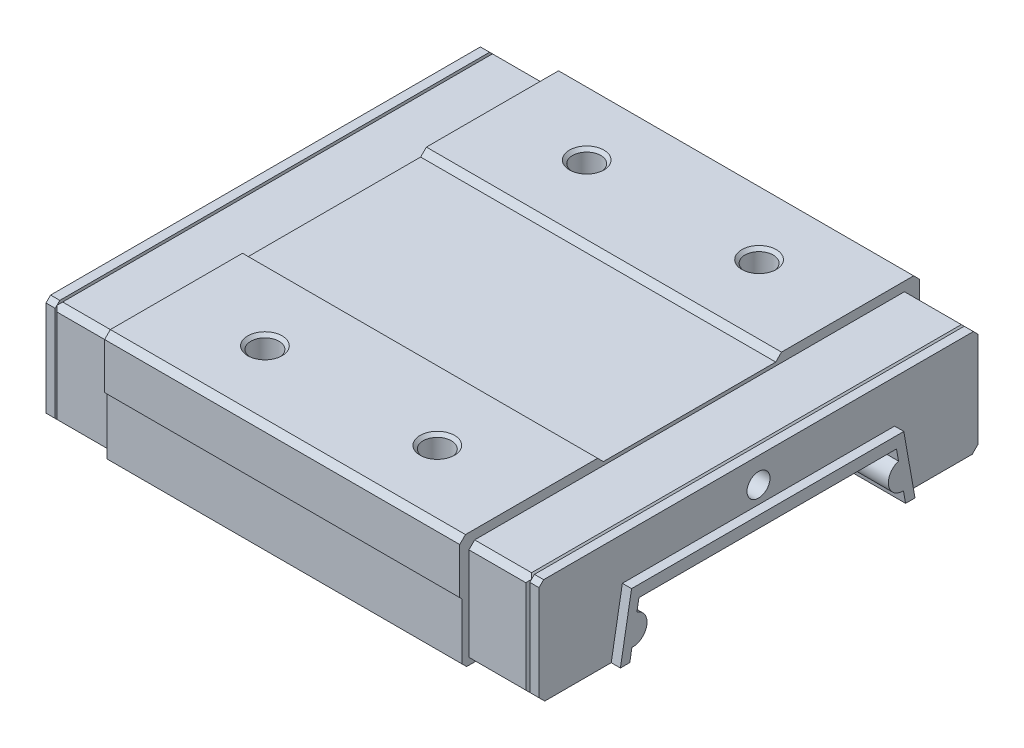
SolidWorks part; units mm, degrees
ref_plane "Plano frontal" through (0, 0, 0) normal (0, 0, 1) x (1, 0, 0)
ref_plane "Plano superior" through (0, 0, 0) normal (0, 1, 0) x (1, 0, 0)
ref_plane "Plano direito" through (0, 0, 0) normal (1, 0, 0) x (0, 0, -1)
ref_plane "Plano1" through (0, 0, 0) normal (1, 0, 0) x (0, 0, -1)
sketch "Esboço1" plane through (0, 0, 0) normal (1, 0, 0) x (0, 0, -1)
  line L0 (-20, 9.5) -> (-20, 5.5)
  line L1 (-20, 5.5) -> (-19.8, 5.3)
  line L2 (-19.8, 5.3) -> (-19.8, 0.4)
  line L3 (-19.8, 0.4) -> (-19.4, 0)
  line L4 (-19.4, 0) -> (19.4, 0)
  line L5 (19.4, 0) -> (19.8, 0.4)
  line L6 (19.8, 0.4) -> (19.8, 5.3)
  line L7 (19.8, 5.3) -> (20, 5.5)
  line L8 (20, 5.5) -> (20, 9.5)
  line L9 (20, 9.5) -> (19.5, 10)
  line L10 (19.5, 10) -> (8, 10)
  line L11 (8, 10) -> (7.5, 9.5)
  line L12 (7.5, 9.5) -> (-7.5, 9.5)
  line L13 (-7.5, 9.5) -> (-8, 10)
  line L14 (-8, 10) -> (-19.5, 10)
  line L15 (-19.5, 10) -> (-20, 9.5)
extrude "Ressalto-extrusão1" add sketch "Esboço1" against normal blind 15.45 and the other way blind 15.45
ref_plane "Plano2" through (-15.45, 0, 0) normal (1, 0, 0) x (0, 0, -1)
sketch "Esboço2" plane through (-15.45, 0, 0) normal (1, 0, 0) x (0, 0, -1)
  line L0 (-19.2, 8.7) -> (-19.2, 0.6)
  line L1 (-19.2, 0.6) -> (-18.6, 0)
  line L2 (-18.6, 0) -> (18.6, 0)
  line L3 (18.6, 0) -> (19.2, 0.6)
  line L4 (19.2, 0.6) -> (19.2, 8.7)
  line L5 (19.2, 8.7) -> (18.7, 9.2)
  line L6 (18.7, 9.2) -> (-18.7, 9.2)
  line L7 (-18.7, 9.2) -> (-19.2, 8.7)
extrude "Ressalto-extrusão2" add sketch "Esboço2" against normal blind 6
ref_plane "Plano3" through (15.45, 0, 0) normal (1, 0, 0) x (0, 0, -1)
sketch "Esboço3" plane through (15.45, 0, 0) normal (1, 0, 0) x (0, 0, -1)
  line L0 (-19.2, 8.7) -> (-19.2, 0.6)
  line L1 (-19.2, 0.6) -> (-18.6, 0)
  line L2 (-18.6, 0) -> (18.6, 0)
  line L3 (18.6, 0) -> (19.2, 0.6)
  line L4 (19.2, 0.6) -> (19.2, 8.7)
  line L5 (19.2, 8.7) -> (18.7, 9.2)
  line L6 (18.7, 9.2) -> (-18.7, 9.2)
  line L7 (-18.7, 9.2) -> (-19.2, 8.7)
extrude "Ressalto-extrusão3" add sketch "Esboço3" along normal blind 6
ref_plane "Plano4" through (0, 0, 0) normal (1, 0, 0) x (0, 0, -1)
sketch "Esboço4" plane through (0, 0, 0) normal (1, 0, 0) x (0, 0, -1)
  line L0 (-12.816, 0) -> (12.816, 0)
  line L1 (12.816, 0) -> (11.8462, 5.5)
  line L2 (11.8462, 5.5) -> (-11.8462, 5.5)
  line L3 (-11.8462, 5.5) -> (-12.816, 0)
extrude "Ressalto-extrusão4" add sketch "Esboço4" against normal blind 22.25 and the other way blind 22.25
ref_plane "Plano5" through (0, 0, 0) normal (1, 0, 0) x (0, 0, -1)
sketch "Esboço5" plane through (0, 0, 0) normal (1, 0, 0) x (0, 0, -1)
  line L0 (-12, 0) -> (12, 0)
  line L1 (12, 0) -> (11.8146, 1.0517)
  line L2 (11.3837, 3.4951) -> (11.2065, 4.5)
  line L3 (11.2065, 4.5) -> (-11.2065, 4.5)
  line L4 (-11.2065, 4.5) -> (-11.3837, 3.4951)
  line L5 (-11.8146, 1.0517) -> (-12, 0)
  arc A0 (11.8146, 1.0517) -> (11.3837, 3.4951) centre (11.75, 2.3) cw
  arc A1 (-11.3837, 3.4951) -> (-11.8146, 1.0517) centre (-11.75, 2.3) cw
extrude "Corte-extrusão1" cut sketch "Esboço5" against normal blind 22.25 and the other way blind 22.25
ref_plane "Plano6" through (0, 0, 14) normal (0, 0, 1) x (1, 0, 0)
sketch "Esboço6" plane through (0, 0, 14) normal (0, 0, 1) x (1, 0, 0)
  line L0 (7.5, 10) -> (9, 10)
  line L1 (9, 10) -> (8.7295, 9.7295)
  line L2 (8.7295, 9.7295) -> (8.7295, 5.8)
  line L3 (8.7295, 5.8) -> (7.5, 5.0901)
  line L4 (7.5, 5.0901) -> (7.5, 10)
  line L5 (7.5, 5.0901) -> (7.5, 10) construction
revolve "Corte-Revolução1" cut sketch "Esboço6" angle 360 about L5
ref_plane "Plano7" through (0, 0, -14) normal (0, 0, 1) x (1, 0, 0)
sketch "Esboço7" plane through (0, 0, -14) normal (0, 0, 1) x (1, 0, 0)
  line L0 (-7.5, 10) -> (-6, 10)
  line L1 (-6, 10) -> (-6.2705, 9.7295)
  line L2 (-6.2705, 9.7295) -> (-6.2705, 5.8)
  line L3 (-6.2705, 5.8) -> (-7.5, 5.0901)
  line L4 (-7.5, 5.0901) -> (-7.5, 10)
  line L5 (-7.5, 5.0901) -> (-7.5, 10) construction
revolve "Corte-Revolução2" cut sketch "Esboço7" angle 360 about L5
ref_plane "Plano8" through (0, 0, 14) normal (0, 0, 1) x (1, 0, 0)
sketch "Esboço8" plane through (0, 0, 14) normal (0, 0, 1) x (1, 0, 0)
  line L0 (-7.5, 10) -> (-6, 10)
  line L1 (-6, 10) -> (-6.2705, 9.7295)
  line L2 (-6.2705, 9.7295) -> (-6.2705, 5.8)
  line L3 (-6.2705, 5.8) -> (-7.5, 5.0901)
  line L4 (-7.5, 5.0901) -> (-7.5, 10)
  line L5 (-7.5, 5.0901) -> (-7.5, 10) construction
revolve "Corte-Revolução3" cut sketch "Esboço8" angle 360 about L5
ref_plane "Plano9" through (0, 0, -14) normal (0, 0, 1) x (1, 0, 0)
sketch "Esboço9" plane through (0, 0, -14) normal (0, 0, 1) x (1, 0, 0)
  line L0 (7.5, 10) -> (9, 10)
  line L1 (9, 10) -> (8.7295, 9.7295)
  line L2 (8.7295, 9.7295) -> (8.7295, 5.8)
  line L3 (8.7295, 5.8) -> (7.5, 5.0901)
  line L4 (7.5, 5.0901) -> (7.5, 10)
  line L5 (7.5, 5.0901) -> (7.5, 10) construction
revolve "Corte-Revolução4" cut sketch "Esboço9" angle 360 about L5
ref_plane "Plano10" through (0, 0, 0) normal (0, 1, 0) x (1, 0, 0)
sketch "Esboço10" plane through (0, 0, 0) normal (0, 1, 0) x (1, 0, 0)
  line L0 (-24.25, -22) -> (24.25, -22)
  line L1 (24.25, -22) -> (24.25, 22)
  line L2 (24.25, 22) -> (-24.25, 22)
  line L3 (-24.25, 22) -> (-24.25, -22)
  line L4 (-23.25, 19.1) -> (-23.25, -19.1)
  line L5 (-23.25, -19.1) -> (-20.65, -19.1)
  line L6 (-20.65, -19.1) -> (-20.65, -21)
  line L7 (-20.65, -21) -> (20.65, -21)
  line L8 (20.65, -21) -> (20.65, -19.1)
  line L9 (20.65, -19.1) -> (23.25, -19.1)
  line L10 (23.25, -19.1) -> (23.25, 19.1)
  line L11 (23.25, 19.1) -> (20.65, 19.1)
  line L12 (20.65, 19.1) -> (20.65, 21)
  line L13 (20.65, 21) -> (-20.65, 21)
  line L14 (-20.65, 21) -> (-20.65, 19.1)
  line L15 (-20.65, 19.1) -> (-23.25, 19.1)
extrude "Corte-extrusão2" cut sketch "Esboço10" along normal blind 11
ref_plane "Plano11" through (0, 0, 0) normal (0, 0, 1) x (1, 0, 0)
sketch "Esboço11" plane through (0, 0, 0) normal (0, 0, 1) x (1, 0, 0)
  line L0 (-20.65, 9.2) -> (-20.65, 8.95)
  line L1 (-20.65, 8.95) -> (-20.4, 9.2)
  line L2 (-20.4, 9.2) -> (-20.65, 9.2)
extrude "Corte-extrusão3" cut sketch "Esboço11" against normal blind 20 and the other way blind 20
ref_plane "Plano12" through (0, 0, 0) normal (0, 0, 1) x (1, 0, 0)
sketch "Esboço12" plane through (0, 0, 0) normal (0, 0, 1) x (1, 0, 0)
  line L0 (20.4, 9.2) -> (20.65, 8.95)
  line L1 (20.65, 8.95) -> (20.65, 9.2)
  line L2 (20.65, 9.2) -> (20.4, 9.2)
extrude "Corte-extrusão4" cut sketch "Esboço12" against normal blind 20 and the other way blind 20
ref_plane "Plano13" through (0, 0, 0) normal (0, 1, 0) x (1, 0, 0)
sketch "Esboço13" plane through (0, 0, 0) normal (0, 1, 0) x (1, 0, 0)
  line L0 (-20.65, 19.2) -> (-20.65, 18.95)
  line L1 (-20.65, 18.95) -> (-20.4, 19.2)
  line L2 (-20.4, 19.2) -> (-20.65, 19.2)
extrude "Corte-extrusão5" cut sketch "Esboço13" along normal blind 10
ref_plane "Plano14" through (0, 0, 0) normal (0, 1, 0) x (1, 0, 0)
sketch "Esboço14" plane through (0, 0, 0) normal (0, 1, 0) x (1, 0, 0)
  line L0 (-20.65, -19.2) -> (-20.4, -19.2)
  line L1 (-20.4, -19.2) -> (-20.65, -18.95)
  line L2 (-20.65, -18.95) -> (-20.65, -19.2)
extrude "Corte-extrusão6" cut sketch "Esboço14" along normal blind 10
ref_plane "Plano15" through (0, 0, 0) normal (0, 1, 0) x (1, 0, 0)
sketch "Esboço15" plane through (0, 0, 0) normal (0, 1, 0) x (1, 0, 0)
  line L0 (20.4, 19.2) -> (20.65, 18.95)
  line L1 (20.65, 18.95) -> (20.65, 19.2)
  line L2 (20.65, 19.2) -> (20.4, 19.2)
extrude "Corte-extrusão7" cut sketch "Esboço15" along normal blind 10
ref_plane "Plano16" through (0, 0, 0) normal (0, 1, 0) x (1, 0, 0)
sketch "Esboço16" plane through (0, 0, 0) normal (0, 1, 0) x (1, 0, 0)
  line L0 (20.4, -19.2) -> (20.65, -19.2)
  line L1 (20.65, -19.2) -> (20.65, -18.95)
  line L2 (20.65, -18.95) -> (20.4, -19.2)
extrude "Corte-extrusão8" cut sketch "Esboço16" along normal blind 10
ref_plane "Plano17" through (0, 0, 0) normal (0, 0, 1) x (1, 0, 0)
sketch "Esboço17" plane through (0, 0, 0) normal (0, 0, 1) x (1, 0, 0)
  line L0 (-21.45, 7) -> (-21.45, 8)
  line L1 (-21.45, 8) -> (-18.95, 8)
  line L2 (-18.95, 8) -> (-18.95, 7)
  line L3 (-18.95, 7) -> (-21.45, 7)
  line L4 (-18.95, 7) -> (-21.45, 7) construction
revolve "Corte-Revolução5" cut sketch "Esboço17" angle 360 about L4
ref_plane "Plano18" through (0, 0, 0) normal (0, 0, 1) x (1, 0, 0)
sketch "Esboço18" plane through (0, 0, 0) normal (0, 0, 1) x (1, 0, 0)
  line L0 (18.95, 7) -> (18.95, 8)
  line L1 (18.95, 8) -> (21.45, 8)
  line L2 (21.45, 8) -> (21.45, 7)
  line L3 (21.45, 7) -> (18.95, 7)
  line L4 (21.45, 7) -> (18.95, 7) construction
revolve "Corte-Revolução6" cut sketch "Esboço18" angle 360 about L4
sketch "Esboço19" plane through (0, 9.5, 0) normal (0, 1, 0) x (1, 0, 0)
  line L0 (15.45, 0) -> (-15.45, 0) construction
  line L1 (15.45, 7.5) -> (15.45, -7.5) construction
  line L2 (-15.45, 7.5) -> (-15.45, -7.5) construction
  line L4 (15.45, -7.5) -> (-15.45, -7.5) construction
  line L5 (0, -7.5) -> (0, 7.5) construction
  line L6 (15.45, 7.5) -> (-15.45, 7.5) construction
  circle A0 centre (0, 0) radius 3.6906
